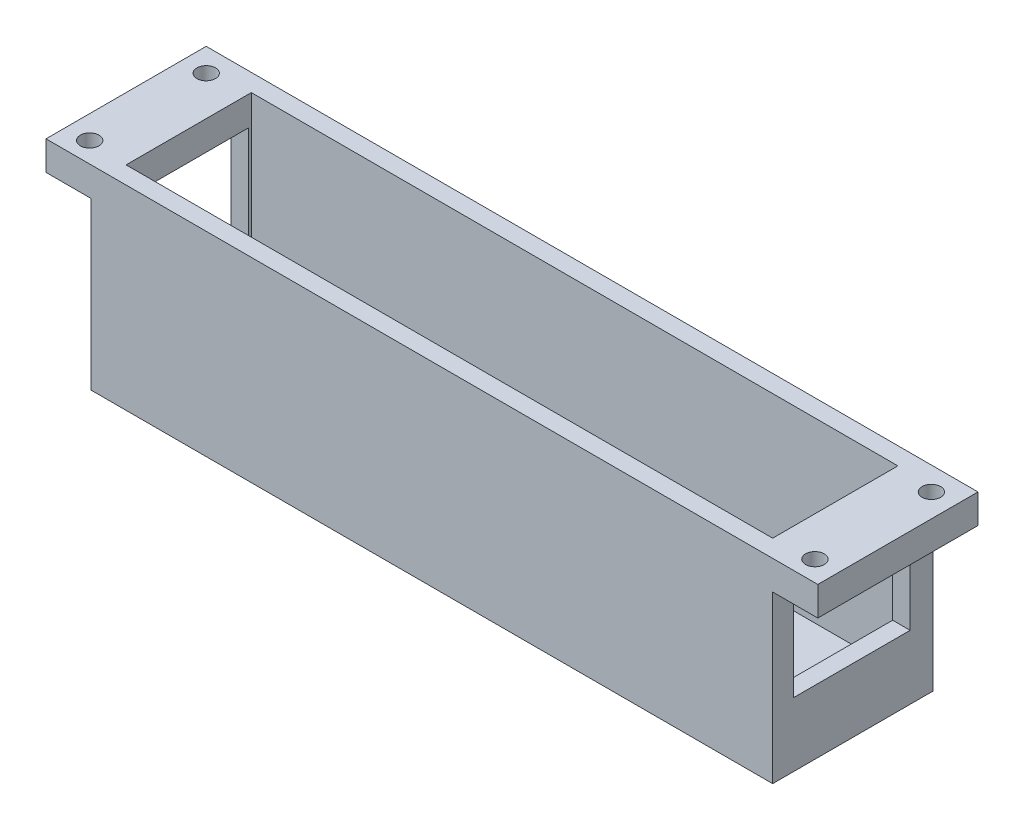
SolidWorks part; units mm, degrees
ref_plane "Płaszczyzna przednia" through (0, 0, 0) normal (0, 0, 1) x (1, 0, 0)
ref_plane "Płaszczyzna górna" through (0, 0, 0) normal (0, 1, 0) x (1, 0, 0)
ref_plane "Płaszczyzna prawa" through (0, 0, 0) normal (1, 0, 0) x (0, 0, -1)
sketch "Szkic1" plane through (0, 0, 0) normal (0, 0, 1) x (1, 0, 0)
  line L1 (0, 0) -> (117, 0)
  line L2 (0, 0) -> (0, 28.5)
  line L4 (117, 0) -> (117, 28.5)
  line L5 (-7.75, 33.5) -> (-7.75, 28.5)
  line L6 (-7.75, 28.5) -> (0, 28.5)
  line L8 (124.75, 33.5) -> (124.75, 28.5)
  line L9 (124.75, 28.5) -> (117, 28.5)
  line L10 (124.75, 33.5) -> (-7.75, 33.5)
  dimension "D1" = 117
  dimension "D2" = 132.5
  dimension "D3" = 7.75
  dimension "D4" = 28.5
  dimension "D5" = 5
  dimension "D6" = 5
extrude "Dodanie-wyciągnięcie1" add sketch "Szkic1" along normal blind 27.5
sketch "Szkic2" plane through (0, 33.5, 0) normal (0, 1, 0) x (1, 0, 0)
  line L0 (124.75, 0) -> (-7.75, 0) construction
  line L1 (3, -3) -> (114, -3)
  line L2 (3, -3) -> (3, -24.5)
  line L3 (3, -24.5) -> (114, -24.5)
  line L4 (114, -3) -> (114, -24.5)
  line L5 (124.75, -27.5) -> (124.75, 0) construction
  dimension "D1" = 21.5
  dimension "D2" = 111
  dimension "D3" = 3
  dimension "D4" = 10.75
extrude "Wytnij-wyciągnięcie1" cut sketch "Szkic2" against normal offset from surface (30.5 mm away) 3 up to face at (58.5, 0, 13.75)
sketch "Szkic3" plane through (117, 0, 0) normal (1, 0, 0) x (0, 0, -1)
  line L0 (-27.5, 0) -> (-27.5, 28.5) construction
  line L1 (-23.9, 26) -> (-3.9, 26)
  line L2 (-23.9, 26) -> (-23.9, 11)
  line L3 (-23.9, 11) -> (-3.9, 11)
  line L4 (-3.9, 26) -> (-3.9, 11)
  line L5 (-27.5, 0) -> (0, 0) construction
  dimension "D1" = 20
  dimension "D2" = 15
  dimension "D3" = 3.6
  dimension "D4" = 11
extrude "Wytnij-wyciągnięcie2" cut sketch "Szkic3" against normal blind 3
sketch "Szkic4" plane through (0, 0, 0) normal (-1, 0, 0) x (0, 0, 1)
  line L0 (27.5, 0) -> (0, 0) construction
  line L1 (3.5, 28.5) -> (24, 28.5)
  line L2 (3.5, 28.5) -> (3.5, 8.5)
  line L3 (3.5, 8.5) -> (24, 8.5)
  line L4 (24, 28.5) -> (24, 8.5)
  line L5 (0, 28.5) -> (0, 0) construction
  dimension "D1" = 20.5
  dimension "D2" = 20
  dimension "D3" = 8.5
  dimension "D4" = 3.5
extrude "Wytnij-wyciągnięcie3" cut sketch "Szkic4" against normal blind 3
sketch "Szkic5" plane through (0, 33.5, 0) normal (0, 1, 0) x (1, 0, 0)
  line L0 (124.75, 0) -> (-7.75, 0) construction
  line L1 (-7.75, -27.5) -> (-7.75, 0) construction
  circle A0 centre (-3.75, -4) radius 1.6
  circle A1 centre (120.75, -4) radius 1.6
  circle A2 centre (120.75, -24) radius 1.6
  circle A3 centre (-3.75, -24) radius 1.6
  dimension "D1" = 3.2
  dimension "D3" = 4
  dimension "D2" = 4
  dimension "D4" = 2
  dimension "D5" = 2
extrude "Wytnij-wyciągnięcie4" cut sketch "Szkic5" against normal through all
